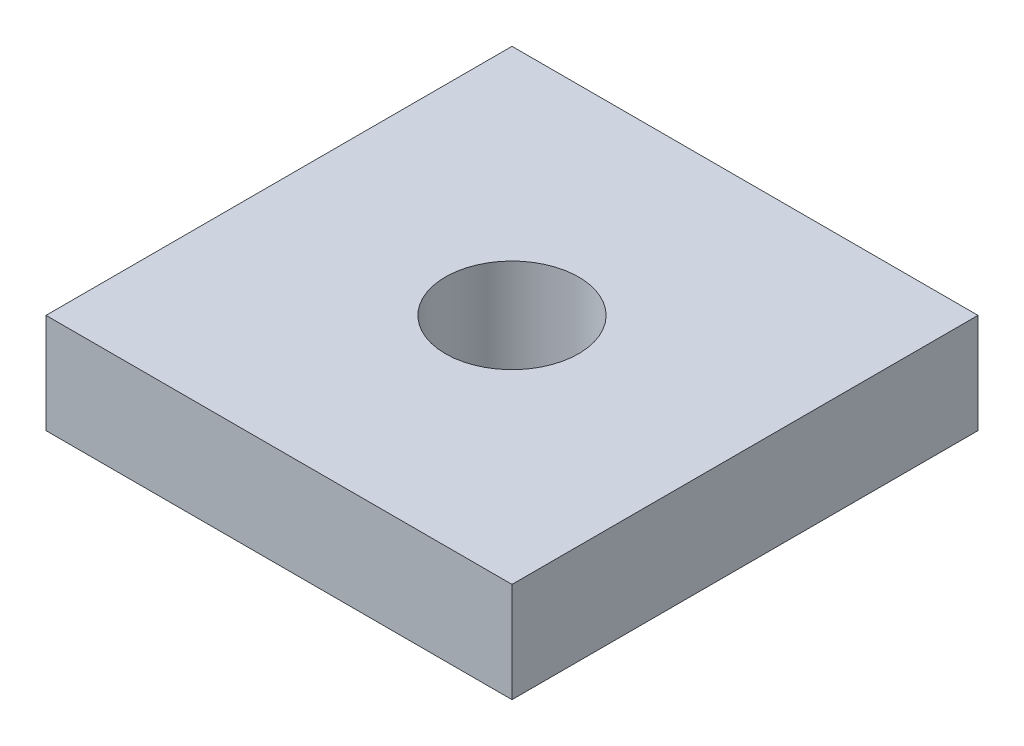
SolidWorks part; units mm, degrees
ref_plane "Front Plane" through (0, 0, 0) normal (0, 0, 1) x (1, 0, 0)
ref_plane "Top Plane" through (0, 0, 0) normal (0, 1, 0) x (1, 0, 0)
ref_plane "Right Plane" through (0, 0, 0) normal (1, 0, 0) x (0, 0, -1)
sketch "Sketch1" plane through (0, 0, 0) normal (0, 1, 0) x (1, 0, 0)
  line L1 (0, 0) -> (44.45, 0)
  line L2 (0, 0) -> (0, -44.45)
  line L3 (0, -44.45) -> (44.45, -44.45)
  line L4 (44.45, 0) -> (44.45, -44.45)
  dimension "D1" = 44.45
  dimension "D2" = 44.45
extrude "Extrude1" add sketch "Sketch1" along normal blind 9.525
ref_plane "Plane1" through (0, 9.525, 0) normal (0, 1, 0) x (-1, 0, 0)
sketch "Sketch3" plane through (0, 9.525, 0) normal (0, 1, 0) x (-1, 0, 0)
  circle A0 centre (-22.225, 22.225) radius 6.35
  dimension "D1" = 12.7
extrude "Cut-Extrude1" cut sketch "Sketch3" against normal blind 9.525
sketch "Sketch4" plane through (0, 9.525, 0) normal (0, 1, 0) x (-1, 0, 0)
  line L0 (-22.225, 22.225) -> (-22.225, 40.137)
  line L1 (-22.225, 22.225) -> (-7.9707, 22.225)
sketch "Sketch5" plane through (0, 0, 0) normal (1, 0, 0) x (0, 0, -1)
  line L0 (-22.225, 4.7625) -> (-37.1468, 4.7625)
  line L1 (0, 0) -> (-44.45, 0) construction
  dimension "D1" = 4.7625
ref_plane "Plane2" through (0, 4.7625, 0) normal (0, -1, 0) x (1, 0, 0)
sketch "Sketch6" plane through (0, 4.7625, 0) normal (0, -1, 0) x (1, 0, 0)
  line L0 (22.225, 22.225) -> (38.7385, 22.225)
sketch "Sketch7" plane through (0, 4.7625, 0) normal (0, -1, 0) x (1, 0, 0)
  line L0 (22.225, 22.225) -> (22.225, 40.137)
  line L1 (22.225, 22.225) -> (7.9707, 22.225)
